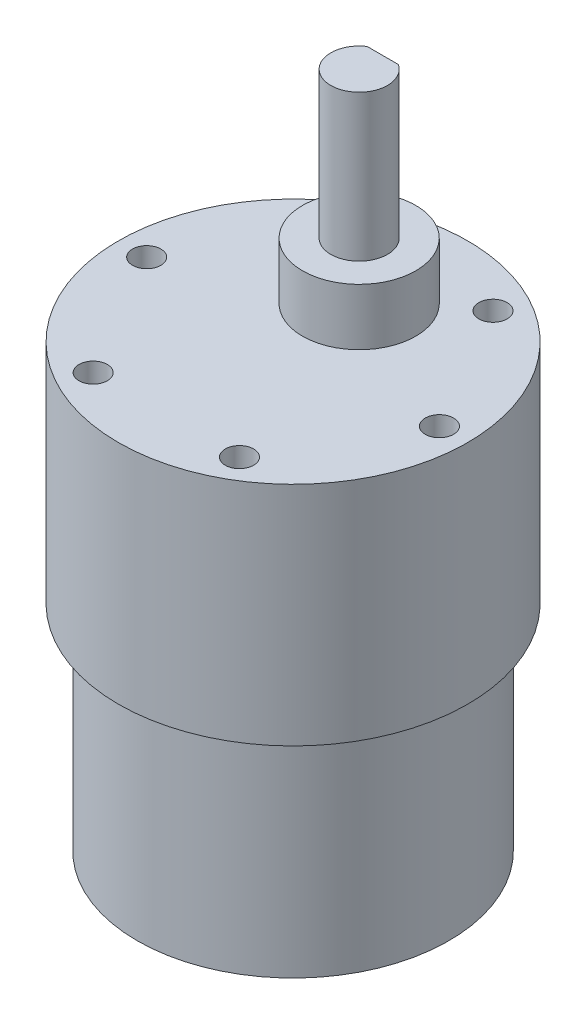
SolidWorks part; units mm, degrees
other "细节项目1"
ref_plane "前视" through (0, 0, 0) normal (0, 0, 1) x (1, 0, 0)
ref_plane "上视" through (0, 0, 0) normal (0, 1, 0) x (1, 0, 0)
ref_plane "右视" through (0, 0, 0) normal (1, 0, 0) x (0, 0, -1)
sketch "草图1" plane through (0, 0, 0) normal (0, 1, 0) x (1, 0, 0)
  circle A0 centre (0, 0) radius 16.5
  dimension "D1" = 33
extrude "凸台-拉伸1" add sketch "草图1" along normal blind 22.7
sketch "草图2" plane through (0, 22.7, 0) normal (0, 1, 0) x (1, 0, 0)
  circle A0 centre (0, 0) radius 18.5
  dimension "D1" = 37
extrude "凸台-拉伸2" add sketch "草图2" along normal blind 24
sketch "草图3" plane through (0, 46.7, 0) normal (0, 1, 0) x (1, 0, 0)
  circle A0 centre (0, 7) radius 6
  point P5 (0, 0)
  dimension "D1" = 12
  dimension "D2" = 7
extrude "凸台-拉伸3" add sketch "草图3" along normal blind 6
sketch "草图4" plane through (0, 52.7, 0) normal (0, 1, 0) x (1, 0, 0)
  circle A0 centre (0, 7) radius 3
  dimension "D1" = 6
extrude "凸台-拉伸4" add sketch "草图4" along normal blind 15.5
sketch "草图5" plane through (0, 68.2, 0) normal (0, 1, 0) x (1, 0, 0)
  line L0 (-1.6583, 9.5) -> (1.6583, 9.5)
  circle A0 centre (0, 7) radius 3
  circle M1 centre (0, 7) radius 3
  dimension "D2" = 6
  dimension "D1" = 2.5
extrude "切除-拉伸1" cut sketch "草图5" against normal blind 12 contours L0 M1 | A0
sketch "草图6" plane through (0, 46.7, 0) normal (0, 1, 0) x (1, 0, 0)
  circle A0 centre (0, 0) radius 15.5 construction
  circle A1 centre (15.5, 0) radius 1.5
  circle A2 centre (7.75, -13.4234) radius 1.5
  circle A3 centre (-7.75, -13.4234) radius 1.5
  circle A4 centre (-15.5, 0) radius 1.5
  circle A5 centre (-7.75, 13.4234) radius 1.5
  circle A6 centre (7.75, 13.4234) radius 1.5
  point P17 (0, 0)
  dimension "D1" = 31
  dimension "D2" = 3
  dimension "D3" = 6
extrude "切除-拉伸2" cut sketch "草图6" against normal blind 10
cosmetic thread "装饰螺纹线1" parameters "D2"=3.5
cosmetic thread "装饰螺纹线2" parameters "D2"=3.5
cosmetic thread "装饰螺纹线3" parameters "D2"=3.5
cosmetic thread "装饰螺纹线4" parameters "D2"=3.5
cosmetic thread "装饰螺纹线5" parameters "D2"=3.5
cosmetic thread "装饰螺纹线6" parameters "D2"=3.5
sketch "草图7" plane through (0, 0, 0) normal (0, -1, 0) x (1, 0, 0)
  circle A0 centre (0, 0) radius 5
  dimension "D1" = 10
extrude "凸台-拉伸5" add sketch "草图7" along normal blind 2
fillet "圆角1" radius 0.5 1 edges at (0, -2, -5)
